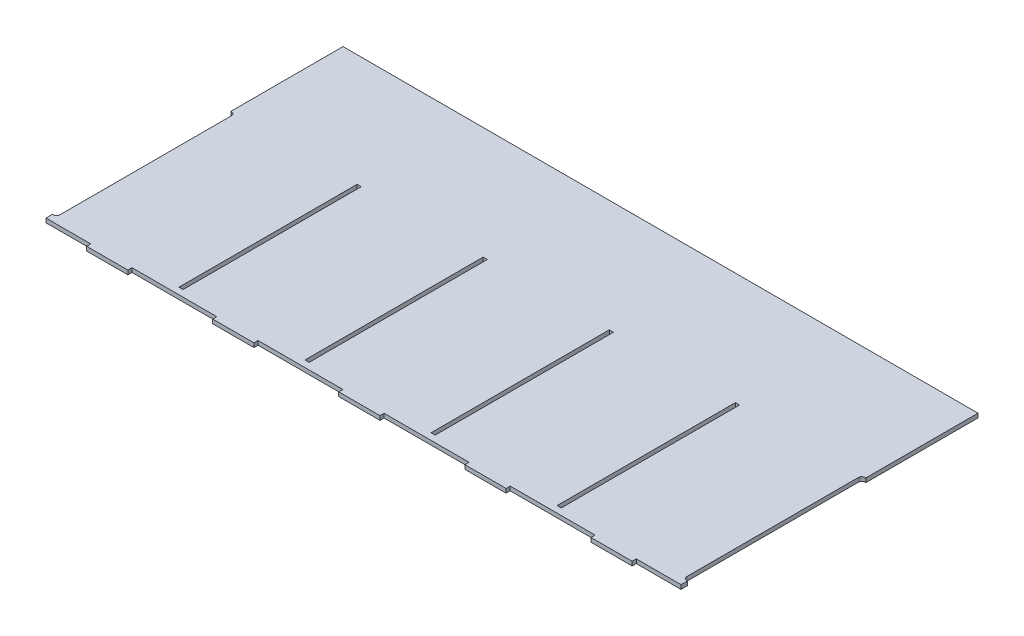
SolidWorks part; units mm, degrees
material "6061-T6 (SS)"
ref_plane "X-Y Datum" through (0, 0, 0) normal (0, 0, 1) x (1, 0, 0)
ref_plane "X-Z Datum" through (0, 0, 0) normal (0, 1, 0) x (1, 0, 0)
ref_plane "Y-Z Datum" through (0, 0, 0) normal (1, 0, 0) x (0, 0, -1)
sketch "Sketch1" plane through (0, 0, 0) normal (0, 1, 0) x (1, 0, 0)
  line L1 (-244.348, 114.3) -> (244.348, 114.3)
  line L2 (-244.348, 114.3) -> (-244.348, 31.75)
  line L3 (-241.173, -114.3) -> (-209.931, -114.3)
  line L4 (244.348, 114.3) -> (244.348, 31.75)
  line L5 (-244.348, 114.3) -> (244.348, -114.3) construction
  line L6 (-244.348, -114.3) -> (244.348, 114.3) construction
  line L8 (0, -43.0151) -> (0, 43.0151) construction
  line L11 (-177.4568, 114.3) -> (-177.4568, 83.0099) construction
  line L28 (-81.153, -114.3) -> (-15.875, -114.3)
  line L29 (15.875, -114.3) -> (81.153, -114.3)
  line L31 (209.931, -114.3) -> (241.173, -114.3)
  line L32 (-244.348, 31.75) -> (-244.348, -114.3)
  line L33 (-244.348, -114.3) -> (-241.173, -114.3)
  line L34 (244.348, 31.75) -> (244.348, -114.3)
  line L35 (244.348, -114.3) -> (241.173, -114.3)
  line L36 (0, 117.475) -> (0, -117.475) construction
  line L37 (-15.875, -114.3) -> (-15.875, -117.475)
  line L41 (-15.875, -117.475) -> (15.875, -117.475)
  line L42 (15.875, -117.475) -> (15.875, -114.3)
  line L43 (112.903, -114.3) -> (178.181, -114.3)
  line L44 (-178.181, -114.3) -> (-112.903, -114.3)
  line L45 (81.153, -114.3) -> (81.153, -117.475)
  line L46 (81.153, -117.475) -> (112.903, -117.475)
  line L47 (112.903, -117.475) -> (112.903, -114.3)
  line L48 (178.181, -114.3) -> (178.181, -117.475)
  line L49 (178.181, -117.475) -> (209.931, -117.475)
  line L50 (209.931, -117.475) -> (209.931, -114.3)
  line L51 (-81.153, -117.475) -> (-81.153, -114.3)
  line L52 (-112.903, -117.475) -> (-81.153, -117.475)
  line L53 (-112.903, -114.3) -> (-112.903, -117.475)
  line L54 (-178.181, -117.475) -> (-178.181, -114.3)
  line L55 (-209.931, -117.475) -> (-178.181, -117.475)
  line L56 (-209.931, -114.3) -> (-209.931, -117.475)
  point P0 (0, 0)
  point P15 (0, 0)
  point P16 (-241.173, 31.75)
  point P19 (241.173, 31.75)
  point P22 (-203.073, -114.3)
  point P23 (-171.323, -114.3)
  dimension "D5" = 15.875
  dimension "D6" = 15.875
  dimension "D1" = 488.696
  dimension "D2" = 228.6
  dimension "D3" = 3.175
  dimension "D4" = 146.05
  dimension "D7" = 3.175
  dimension "D8" = 3
  dimension "D9" = 3
extrude "Boss-Extrude1" add sketch "Sketch1" along normal blind 3.175
sketch "Sketch2" plane through (0, 3.175, 0) normal (0, 1, 0) x (1, 0, 0)
  line L1 (209.931, -114.3) -> (244.348, -114.3) construction
  line L11 (244.348, 27.94) -> (243.713, 27.94)
  line L12 (244.348, -114.3) -> (244.348, 114.3) construction
  line L13 (241.173, 25.4) -> (241.173, -106.68)
  line L14 (243.713, -109.22) -> (244.348, -109.22)
  line L15 (244.348, -109.22) -> (244.348, 27.94)
  line L16 (0, -43.0151) -> (0, 43.0151) construction
  line L17 (-243.713, -109.22) -> (-244.348, -109.22)
  line L18 (-244.348, -109.22) -> (-244.348, 27.94)
  line L19 (-241.173, 25.4) -> (-241.173, -106.68)
  line L20 (-244.348, 27.94) -> (-243.713, 27.94)
  arc A0 (241.173, -106.68) -> (243.713, -109.22) centre (243.713, -106.68) ccw
  arc A1 (243.713, 27.94) -> (241.173, 25.4) centre (243.713, 25.4) ccw
  arc A2 (-243.713, -109.22) -> (-241.173, -106.68) centre (-243.713, -106.68) ccw
  arc A3 (-241.173, 25.4) -> (-243.713, 27.94) centre (-243.713, 25.4) ccw
  point P9 (-220.345, 31.75)
  point P13 (241.173, -109.22)
  point P18 (241.173, 27.94)
  point P21 (-241.173, -109.22)
  point P25 (-241.173, 27.94)
  dimension "D3" = 142.24
  dimension "D2" = 2.54
  dimension "D1" = 3.175
  dimension "D4" = 5.08
extrude "Cut-Extrude1" cut sketch "Sketch2" against normal through all both and the other way through all
sketch "Sketch3" plane through (0, 3.175, 0) normal (0, 1, 0) x (1, 0, 0)
  line L0 (-178.181, -114.3) -> (-112.903, -114.3) construction
  line L5 (-134.493, -112.2509) -> (-134.493, 114.3) construction
  line L6 (244.348, 114.3) -> (-244.348, 114.3) construction
  line L21 (-136.0805, 25.4) -> (-136.0805, -106.68)
  line L23 (-132.9055, 25.4) -> (-132.9055, -106.68)
  line L36 (-134.493, -112.2509) -> (-134.493, -114.3) construction
  line L39 (-136.0805, 25.4) -> (-136.0805, 27.94)
  line L40 (-136.0805, 27.94) -> (-132.9055, 27.94)
  line L41 (-132.9055, 27.94) -> (-132.9055, 25.4)
  line L42 (-136.0805, -106.68) -> (-136.0805, -109.22)
  line L43 (-136.0805, -109.22) -> (-132.9055, -109.22)
  line L44 (-132.9055, -109.22) -> (-132.9055, -106.68)
  line L45 (-46.4185, 27.94) -> (-43.2435, 27.94)
  line L46 (-46.4185, 25.4) -> (-46.4185, 27.94)
  line L47 (-43.2435, 27.94) -> (-43.2435, 25.4)
  line L48 (-46.4185, 25.4) -> (-46.4185, -106.68)
  line L49 (-43.2435, 25.4) -> (-43.2435, -106.68)
  line L50 (-46.4185, -106.68) -> (-46.4185, -109.22)
  line L51 (-43.2435, -109.22) -> (-43.2435, -106.68)
  line L52 (-46.4185, -109.22) -> (-43.2435, -109.22)
  line L53 (43.2435, 27.94) -> (46.4185, 27.94)
  line L54 (43.2435, 25.4) -> (43.2435, 27.94)
  line L55 (46.4185, 27.94) -> (46.4185, 25.4)
  line L56 (43.2435, 25.4) -> (43.2435, -106.68)
  line L57 (46.4185, 25.4) -> (46.4185, -106.68)
  line L58 (43.2435, -106.68) -> (43.2435, -109.22)
  line L59 (46.4185, -109.22) -> (46.4185, -106.68)
  line L60 (43.2435, -109.22) -> (46.4185, -109.22)
  line L61 (132.9055, 27.94) -> (136.0805, 27.94)
  line L62 (132.9055, 25.4) -> (132.9055, 27.94)
  line L63 (136.0805, 27.94) -> (136.0805, 25.4)
  line L64 (132.9055, 25.4) -> (132.9055, -106.68)
  line L65 (136.0805, 25.4) -> (136.0805, -106.68)
  line L66 (132.9055, -106.68) -> (132.9055, -109.22)
  line L67 (136.0805, -109.22) -> (136.0805, -106.68)
  line L68 (132.9055, -109.22) -> (136.0805, -109.22)
  line L69 (-145.542, -114.3) -> (-145.542, 114.3) construction
  point P13 (-124.968, 31.75)
  point P16 (-144.018, 31.75)
  point P17 (-144.018, -109.22)
  point P20 (-124.968, 27.94)
  point P23 (-144.018, 27.94)
  dimension "D3" = 137.16
  dimension "D4" = 1.5875
  dimension "D5" = 4
  dimension "D1" = 142.24
  dimension "D2" = 1.5875
extrude "Cut-Extrude2" [suppressed] cut sketch "Sketch3" against normal through all both and the other way through all
sketch "Sketch4" plane through (0, 3.175, 0) normal (0, 1, 0) x (1, 0, 0)
  line L0 (-145.542, -114.3) -> (-145.542, 114.3) construction
  line L1 (-178.181, -114.3) -> (-112.903, -114.3) construction
  line L2 (244.348, 114.3) -> (-244.348, 114.3) construction
  line L3 (-145.542, 27.94) -> (-147.1295, 27.94)
  line L4 (-147.1295, 27.94) -> (-147.1295, -109.22)
  line L5 (-147.1295, -109.22) -> (-145.542, -109.22)
  line L6 (-145.542, -109.22) -> (-143.9545, -109.22)
  line L7 (-143.9545, -109.22) -> (-143.9545, 27.94)
  line L8 (-143.9545, 27.94) -> (-145.542, 27.94)
  line L9 (-50.1015, -109.22) -> (-48.514, -109.22)
  line L10 (-50.1015, 27.94) -> (-50.1015, -109.22)
  line L11 (-48.514, -109.22) -> (-46.9265, -109.22)
  line L12 (-46.9265, -109.22) -> (-46.9265, 27.94)
  line L13 (-46.9265, 27.94) -> (-48.514, 27.94)
  line L14 (-48.514, 27.94) -> (-50.1015, 27.94)
  line L15 (46.9265, -109.22) -> (48.514, -109.22)
  line L16 (46.9265, 27.94) -> (46.9265, -109.22)
  line L17 (48.514, -109.22) -> (50.1015, -109.22)
  line L18 (50.1015, -109.22) -> (50.1015, 27.94)
  line L19 (50.1015, 27.94) -> (48.514, 27.94)
  line L20 (48.514, 27.94) -> (46.9265, 27.94)
  line L21 (143.9545, -109.22) -> (145.542, -109.22)
  line L22 (143.9545, 27.94) -> (143.9545, -109.22)
  line L23 (145.542, -109.22) -> (147.1295, -109.22)
  line L24 (147.1295, -109.22) -> (147.1295, 27.94)
  line L25 (147.1295, 27.94) -> (145.542, 27.94)
  line L26 (145.542, 27.94) -> (143.9545, 27.94)
  dimension "D1" = 1.5875
  dimension "D2" = 3.175
  dimension "D3" = 142.24
  dimension "D4" = 137.16
  dimension "D5" = 4
extrude "Cut-Extrude3" cut sketch "Sketch4" against normal through all both
